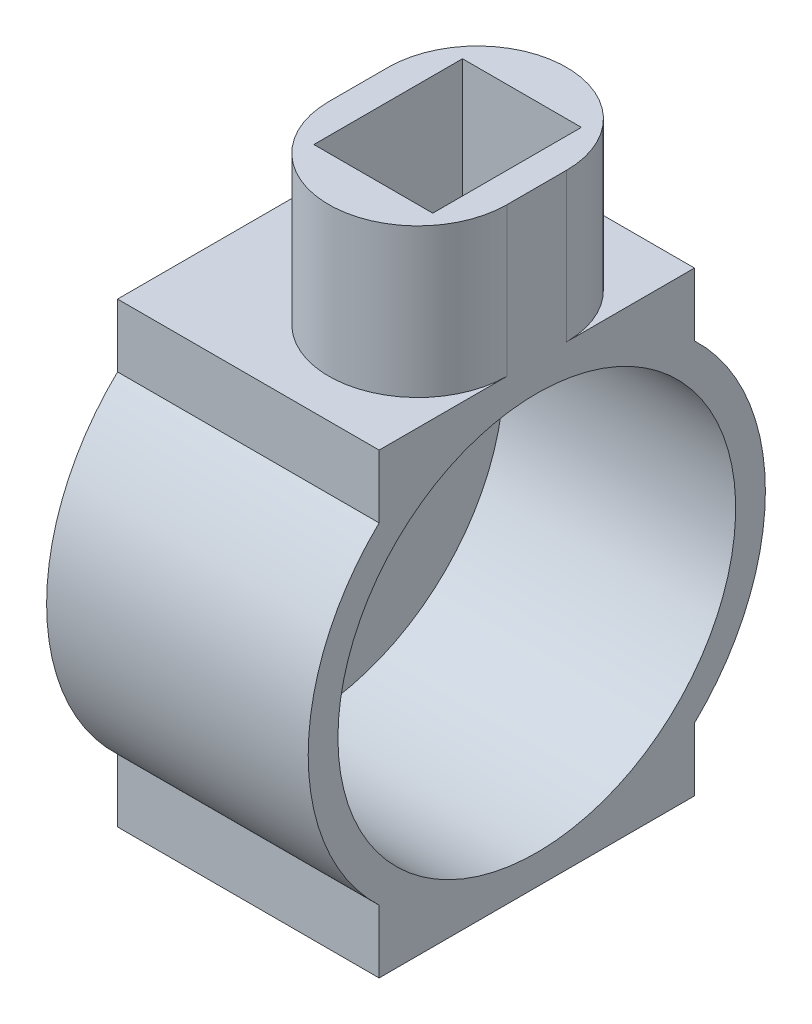
SolidWorks part; units mm, degrees
ref_plane "Front Plane" through (0, 0, 0) normal (0, 0, 1) x (1, 0, 0)
ref_plane "Top Plane" through (0, 0, 0) normal (0, 1, 0) x (1, 0, 0)
ref_plane "Right Plane" through (0, 0, 0) normal (1, 0, 0) x (0, 0, -1)
sketch "Sketch1" plane through (0, 0, 0) normal (1, 0, 0) x (0, 0, -1)
  circle A0 centre (0, 0) radius 38.45
  dimension "D1" = 76.9
extrude "Boss-Extrude1" add sketch "Sketch1" along normal mid plane 111
shell "Shell1" thickness 5
ref_plane "Plane1" through (0, 38.45, 0) normal (0, 1, 0) x (1, 0, 0)
sketch "Sketch2" plane through (0, 38.45, 0) normal (0, 1, 0) x (1, 0, 0)
  line L0 (-55.5, 38.45) -> (-55.5, -38.45) construction
  line L1 (-55.5, 26.52) -> (55.5, 26.52)
  line L2 (-55.5, 26.52) -> (-55.5, -26.52)
  line L3 (-55.5, -26.52) -> (55.5, -26.52)
  line L4 (55.5, 26.52) -> (55.5, -26.52)
  line L5 (55.5, -38.45) -> (55.5, 38.45) construction
  point P8 (55.5, 0)
  dimension "D1" = 53.04
extrude "Boss-Extrude2" add sketch "Sketch2" against normal up to surface (10.6095 mm away)
mirror "Mirror1" about plane through (0, 0, 0) normal (0, 1, 0) of "Boss-Extrude2"
sketch "Sketch3" plane through (0, 38.45, 0) normal (0, 1, 0) x (1, 0, 0)
  line L0 (-50.5, 26.52) -> (-50.5, -26.52) construction
  line L1 (55.5, 26.52) -> (-55.5, 26.52) construction
  line L2 (-55.5, -26.52) -> (55.5, -26.52) construction
  line L3 (-55.5, 26.52) -> (-55.5, -26.52) construction
  line L5 (-36.5, 12.5) -> (-16.5, 12.5)
  line L6 (-36.5, 12.5) -> (-36.5, -12.5)
  line L7 (-36.5, -12.5) -> (-16.5, -12.5)
  line L8 (-16.5, 12.5) -> (-16.5, -12.5)
  point P12 (-16.5, 0)
  dimension "D1" = 5
  dimension "D2" = 14
  dimension "D3" = 25
  dimension "D4" = 20
extrude "Cut-Extrude1" cut sketch "Sketch3" against normal up to next
ref_plane "Plane2" through (0, 38.55, 0) normal (0, 1, 0) x (1, 0, 0)
sketch "Sketch5" plane through (0, 38.45, 0) normal (0, 1, 0) x (1, 0, 0)
  line L0 (-26.5, 5) -> (-26.5, -5) construction
  line L1 (-11.5, 5) -> (-11.5, -5)
  line L2 (-41.5, 5) -> (-41.5, -5)
  line L3 (-26.5, 20) -> (-26.5, -20) construction
  line L4 (-36.5, 0) -> (-16.5, 0) construction
  line L5 (-36.5, 12.5) -> (-36.5, -12.5) construction
  line L6 (-16.5, 12.5) -> (-16.5, -12.5) construction
  arc A0 (-11.5, 5) -> (-41.5, 5) centre (-26.5, 5) ccw
  arc A1 (-41.5, -5) -> (-11.5, -5) centre (-26.5, -5) ccw
  point P2 (-26.5, 0)
  dimension "D1" = 30
  dimension "D2" = 40
extrude "Boss-Extrude5" add sketch "Sketch5" along normal blind 25
sketch "Sketch6" plane through (0, 63.45, 0) normal (0, 1, 0) x (1, 0, 0)
  line L4 (-16.5, 12.5) -> (-36.5, 12.5)
  line L5 (-16.5, -12.5) -> (-16.5, 12.5)
  line L6 (-36.5, -12.5) -> (-16.5, -12.5)
  line L7 (-36.5, 12.5) -> (-36.5, -12.5)
  line L8 (-16.5, 12.5) -> (-36.5, 12.5)
  line L9 (-16.5, -12.5) -> (-16.5, 12.5)
  line L10 (-36.5, -12.5) -> (-16.5, -12.5)
  line L11 (-36.5, 12.5) -> (-36.5, -12.5)
  dimension "D1" = 0
extrude "Cut-Extrude2" cut sketch "Sketch6" against normal up to next
sketch "Sketch7" plane through (0, 38.45, 0) normal (0, 1, 0) x (1, 0, 0)
  line L0 (55.5, 38.45) -> (-55.5, 38.45) construction
  line L1 (-11.5, 38.45) -> (55.5, 38.45)
  line L2 (-11.5, 38.45) -> (-11.5, -38.45)
  line L3 (-11.5, -38.45) -> (55.5, -38.45)
  line L4 (55.5, 38.45) -> (55.5, -38.45)
  line L5 (-11.5, -5) -> (-11.5, 5) construction
extrude "Cut-Extrude3" cut sketch "Sketch7" against normal through all both and the other way through all
equation "\"Can Daimeter\"= 66.3"
equation "\"Can Height\"= 121.6"
equation "\"Bottom of hole to Can bottome\"= 14"
equation "\"D1@Sketch1\"=\"Can Daimeter\"+0.6 +\"Shell Thickness\"*2"
equation "\"Shell Thickness\"= 5"
equation "\"Bottom To flat\"= 106"
equation "\"D1@Boss-Extrude1\"=\"Bottom To flat\"+\"Shell Thickness\""
equation "\"D1@Shell1\"=\"Shell Thickness\""
equation "\"D1@Sketch2\"=\"Can Daimeter\"*0.8"
equation "\"D1@Sketch3\"=\"Shell Thickness\""
equation "\"D2@Sketch3\"=14"
equation "\"Hole Length\"= 25"
equation "\"Hole Height\"= 20"
equation "\"D3@Sketch3\"=\"Hole Length\""
equation "\"D4@Sketch3\"=\"Hole Height\""
equation "\"D1@Sketch5\"=\"Hole Height\"+10"
equation "\"D2@Sketch5\"=\"Hole Length\"+15"
